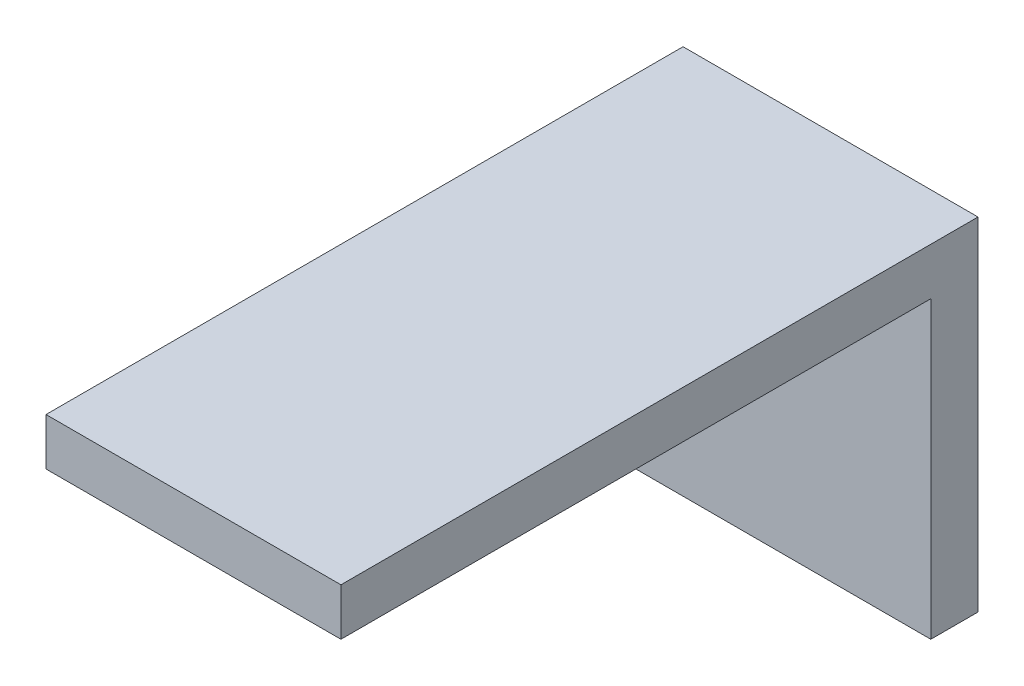
SolidWorks part; units mm, degrees
ref_plane "Top" through (0, 0, 0) normal (0, 0, 1) x (1, 0, 0)
ref_plane "Front" through (0, 0, 0) normal (0, 1, 0) x (1, 0, 0)
ref_plane "Right" through (0, 0, 0) normal (1, 0, 0) x (0, 0, -1)
sketch "Profile Sketch" plane through (0, -31.8928, 3.6423) normal (1, 0, 0) x (0, 1, 0)
  line L0 (31.8928, -3.6423) -> (6.8928, -3.6423)
  line L1 (6.8928, -3.6423) -> (6.8928, -7.6423)
  line L2 (6.8928, -7.6423) -> (35.8928, -7.6423)
  line L3 (31.8928, -3.6423) -> (31.8928, 46.3577)
  line L4 (31.8928, 46.3577) -> (35.8928, 46.3577)
  line L5 (35.8928, 46.3577) -> (35.8928, -7.6423)
  point P2 (0, 0)
  point P6 (36.7743, 36.343)
extrude "Profile Extrude" add sketch "Profile Sketch" along normal mid plane 25
equation "\"M2 Close Fit Hole\"= 2.2"
equation "\"M2.5 Close Fit Hole\"= 2.7"
equation "\"M3 Close Fit Hole\"= 3.2"
equation "\"M4 Close Fit Hole\"= 4.3"
equation "\"M5 Close Fit Hole\"= 5.3"
equation "\"M6 Close Fit Hole\"= 6.3"
equation "\"M7 Close Fit Hole\"= 7.4"
equation "\"M8 Close Fit Hole\"= 8.4"
equation "\"M2 Tap Hole 75%\"= 1.6"
equation "\"M3 Tap Hole 75%\"= 2.5"
equation "\"M4 Tap Hole 75%\"= 3.3"
equation "\"M5 Tap Hole 75%\"= 4.2"
equation "\"M6 Tap Hole 75%\"= 5"
equation "\"M7 Tap Hole 75%\"= 6"
equation "\"M8 Tap Hole 75%\"= 6.8"
equation "\"Bracket Width\"= 25mm"
equation "\"D1@Profile Extrude\"=\"Bracket Width\""
